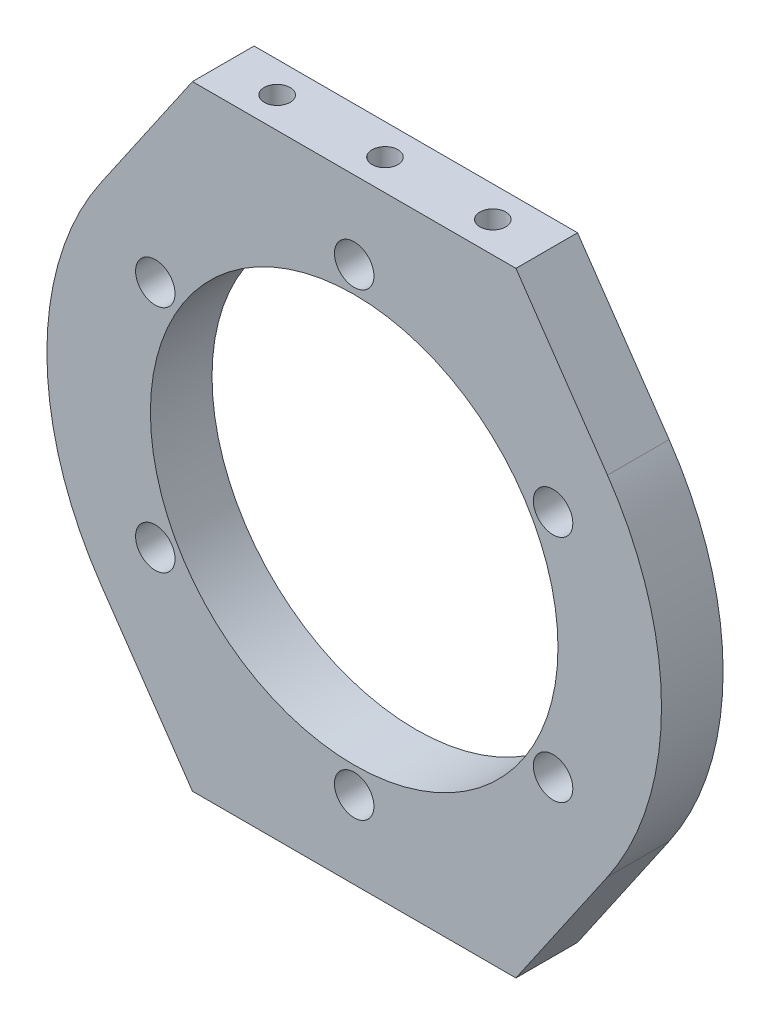
SolidWorks part; units mm, degrees
ref_plane "Front Plane" through (0, 0, 0) normal (0, 0, 1) x (1, 0, 0)
ref_plane "Top Plane" through (0, 0, 0) normal (0, 1, 0) x (1, 0, 0)
ref_plane "Right Plane" through (0, 0, 0) normal (1, 0, 0) x (0, 0, -1)
sketch "Sketch1" plane through (0, 0, 0) normal (0, 0, 1) x (1, 0, 0)
  line L0 (0, 52) -> (0, -52) construction
  line L1 (-47.5, 0) -> (47.5, 0) construction
  line L2 (-25, 47.5) -> (25, 47.5)
  line L3 (-39.154, 26.8926) -> (-25, 47.5)
  line L4 (0, 52) -> (0, 47.5) construction
  line L5 (39.154, 26.8926) -> (25, 47.5)
  line L6 (39.154, -26.8926) -> (25, -47.5)
  line L7 (-25, -47.5) -> (25, -47.5)
  line L8 (-39.154, -26.8926) -> (-25, -47.5)
  arc A0 (-39.154, 26.8926) -> (-39.154, -26.8926) centre (0, 0) ccw
  arc A1 (39.154, -26.8926) -> (39.154, 26.8926) centre (0, 0) ccw
  dimension "D1" = 95
  dimension "D2" = 50
  dimension "D3" = 47.5
extrude "Boss-Extrude1" add sketch "Sketch1" against normal blind 9.525
sketch "Sketch2" plane through (0, 0, 0) normal (0, 0, 1) x (1, 0, 0)
  circle A0 centre (0, 0) radius 35.5 construction
  point P4 (0, 35.5)
  point P8 (30.7439, 17.75)
  point P9 (30.7439, -17.75)
  point P10 (0, -35.5)
  point P11 (-30.7439, -17.75)
  point P12 (-30.7439, 17.75)
  point P13 (0, 0)
  dimension "D1" = 71
  dimension "D2" = 6
hole_wizard "Ø6.0mm Dowel Hole1" positions "Sketch2" profile "Sketch3" hole size "Ø6.0" standard "ANSI Metric"
sketch "Sketch3" plane through (-30.7439, 17.75, 0) normal (1, 0, 0) x (0, -1, 0)
  line L0 (0, 0) -> (0, 9.525)
  line L1 (0, 9.525) -> (3.05, 9.525)
  line L2 (3.05, 9.525) -> (3.05, 0)
  line L5 (3.05, 0) -> (0, 0)
  line L11 (0, -6.35) -> (0, 107.95) construction
  dimension "Thru Hole Dia." = 6.1
  dimension "Thru Hole Depth" = 9.525
sketch "Sketch4" plane through (0, 0, -9.525) normal (0, 0, -1) x (-1, 0, 0)
  circle A0 centre (0, 0) radius 31.5
  dimension "D1" = 63
extrude "Cut-Extrude1" cut sketch "Sketch4" against normal through all
sketch "Sketch5" plane through (0, -47.5, 0) normal (0, -1, 0) x (1, 0, 0)
  point P0 (0, -4.7625)
  point P1 (-16.67, -4.7625)
  point P2 (16.67, -4.7625)
  dimension "D1" = 16.67
  dimension "D2" = 16.67
  dimension "D3" = 4.7625
sketch "Sketch6" plane through (0, 47.5, 0) normal (0, 1, 0) x (1, 0, 0)
  point P0 (-16.67, 4.7625)
  point P2 (0, 4.7625)
  point P4 (16.67, 4.7625)
hole_wizard "Ø4.0mm Dowel Hole1" positions "Sketch6" profile "Sketch7" hole size "Ø4.0" standard "ANSI Metric"
sketch "Sketch7" plane through (-16.67, 47.5, -4.7625) normal (1, 0, 0) x (0, 0, 1)
  line L0 (0, 0) -> (0, 4.4017)
  line L1 (0, 4.4017) -> (2, 3.2)
  line L2 (2, 3.2) -> (2, 0)
  line L5 (2, 0) -> (0, 0)
  line L10 (0, 4.4017) -> (-2, 3.2) construction
  line L11 (0, -6.35) -> (0, 107.95) construction
  dimension "Hole Dia." = 4
  dimension "Hole Depth" = 3.2
  dimension "Drill Angle" = 118
hole_wizard "Ø4.0mm Dowel Hole2" positions "Sketch5" profile "Sketch8" hole size "Ø4.0" standard "ANSI Metric"
sketch "Sketch8" plane through (0, -47.5, -4.7625) normal (1, 0, 0) x (0, 0, -1)
  line L0 (0, 0) -> (0, 4.4017)
  line L1 (0, 4.4017) -> (2, 3.2)
  line L2 (2, 3.2) -> (2, 0)
  line L5 (2, 0) -> (0, 0)
  line L10 (0, 4.4017) -> (-2, 3.2) construction
  line L11 (0, -6.35) -> (0, 107.95) construction
  dimension "Hole Dia." = 4
  dimension "Hole Depth" = 3.2
  dimension "Drill Angle" = 118
